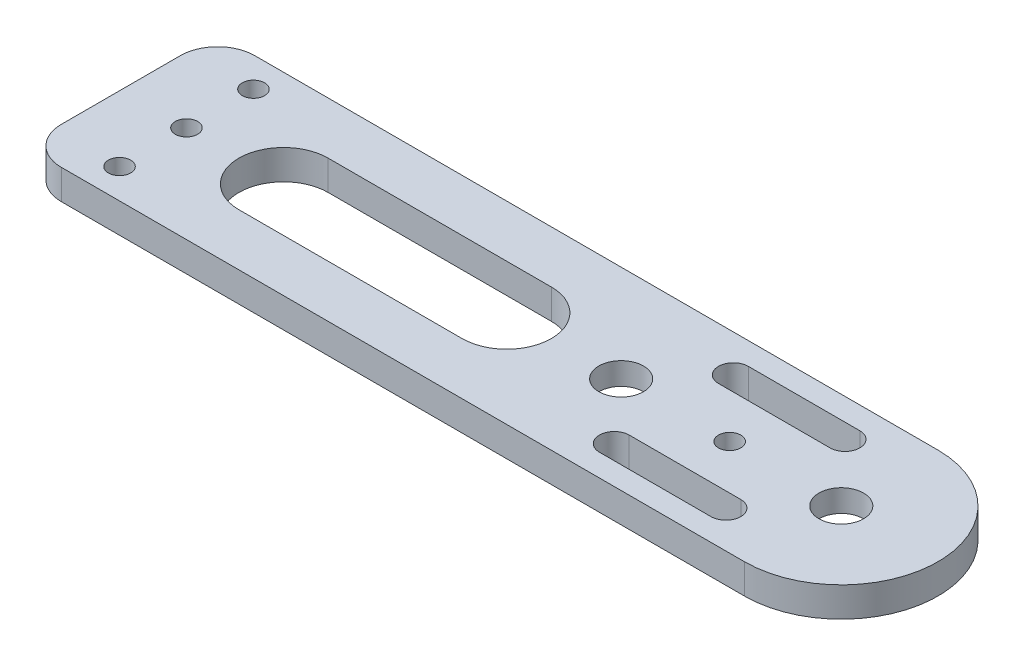
SolidWorks part; units mm, degrees
material "6061-O (SS)"
ref_plane "前视基准面" through (0, 0, 0) normal (0, 0, 1) x (1, 0, 0)
ref_plane "上视基准面" through (0, 0, 0) normal (0, 1, 0) x (1, 0, 0)
ref_plane "右视基准面" through (0, 0, 0) normal (1, 0, 0) x (0, 0, -1)
other "Configuration Table"
sketch "草图1" plane through (0, 0, 0) normal (0, 1, 0) x (1, 0, 0)
  line L0 (0, 0) -> (150, 0) construction
  line L6 (-2.5, -16.7734) -> (-2.5, -6.7734)
  line L7 (-2.5, -16.7734) -> (2.5, -16.7734)
  line L8 (2.5, -16.7734) -> (2.5, -6.7734)
  line L9 (-2.5, -6.7734) -> (2.5, -6.7734)
  line L10 (-2.5, -16.7734) -> (2.5, -6.7734) construction
  line L11 (2.5, -16.7734) -> (-2.5, -6.7734) construction
  line L24 (105.0415, 0) -> (75.0415, 0) construction
  line L25 (105.0415, -6) -> (75.0415, -6)
  line L26 (105.0415, 6) -> (75.0415, 6)
  line L27 (150, 13) -> (15.1987, 13)
  line L28 (150, -13) -> (15.1987, -13)
  line L29 (142.5, 8) -> (127.5, 8) construction
  line L30 (142.5, 6) -> (127.5, 6)
  line L31 (142.5, 10) -> (127.5, 10)
  line L32 (142.5, -8) -> (127.5, -8) construction
  line L33 (142.5, -6) -> (127.5, -6)
  line L34 (142.5, -10) -> (127.5, -10)
  circle A2 centre (0, 0) radius 5
  circle A3 centre (150, 0) radius 3
  circle A4 centre (120.4195, 0) radius 3
  circle A6 centre (0, 9) radius 1.3
  circle A7 centre (7.7942, -4.5) radius 1.3
  circle A8 centre (-7.7942, -4.5) radius 1.3
  arc A15 (150, -13) -> (150, 13) centre (150, 0) ccw
  arc A18 (105.0415, -6) -> (105.0415, 6) centre (105.0415, 0) ccw
  arc A19 (75.0415, 6) -> (75.0415, -6) centre (75.0415, 0) ccw
  circle A20 centre (135, 0) radius 1.5
  circle A21 centre (62, 0) radius 1.5
  circle A22 centre (62, 9) radius 1.5
  circle A23 centre (62, -9) radius 1.5
  arc A25 (15.1987, 13) -> (15.1987, -13) centre (0, 0) ccw
  arc A26 (142.5, 6) -> (142.5, 10) centre (142.5, 8) ccw
  arc A27 (127.5, 10) -> (127.5, 6) centre (127.5, 8) ccw
  arc A28 (142.5, -6) -> (142.5, -10) centre (142.5, -8) cw
  arc A29 (127.5, -10) -> (127.5, -6) centre (127.5, -8) cw
  point P5 (75, 0)
  point P9 (9.7734, 0)
  point P23 (0, 0)
  point P35 (90.0415, 0)
  point P50 (135, 8)
  point P57 (135, -8)
  dimension "D1" = 3
extrude "凸台-拉伸1" add sketch "草图1" along normal blind 4
sketch "草图2" plane through (0, 0, 0) normal (0, -1, 0) x (1, 0, 0)
  circle A0 centre (150, 0) radius 6.01
  circle A1 centre (120.4195, 0) radius 6.01
extrude "切除-拉伸1" cut sketch "草图2" against normal blind 1
ref_point "点1"
sketch "草图4" plane through (0, 4, 0) normal (0, 1, 0) x (1, 0, 0)
  line L1 (-28.0991, 23.044) -> (53.1782, 23.044)
  line L2 (-28.0991, 23.044) -> (-28.0991, -23.1422)
  line L3 (-28.0991, -23.1422) -> (53.1782, -23.1422)
  line L4 (53.1782, 23.044) -> (53.1782, -23.1422)
  line L5 (12.5396, -23.1422) -> (12.5396, 23.044) construction
  line L6 (-28.0991, -0.0491) -> (53.1782, -0.0491) construction
  point P0 (12.5396, -0.0491)
extrude "切除-拉伸4" cut sketch "草图4" against normal blind 16 contours L2 L1 L4 L3
fillet "圆角1" radius 5 2 edges at (53.1782, 2, -13) (53.1782, 2, 13)
